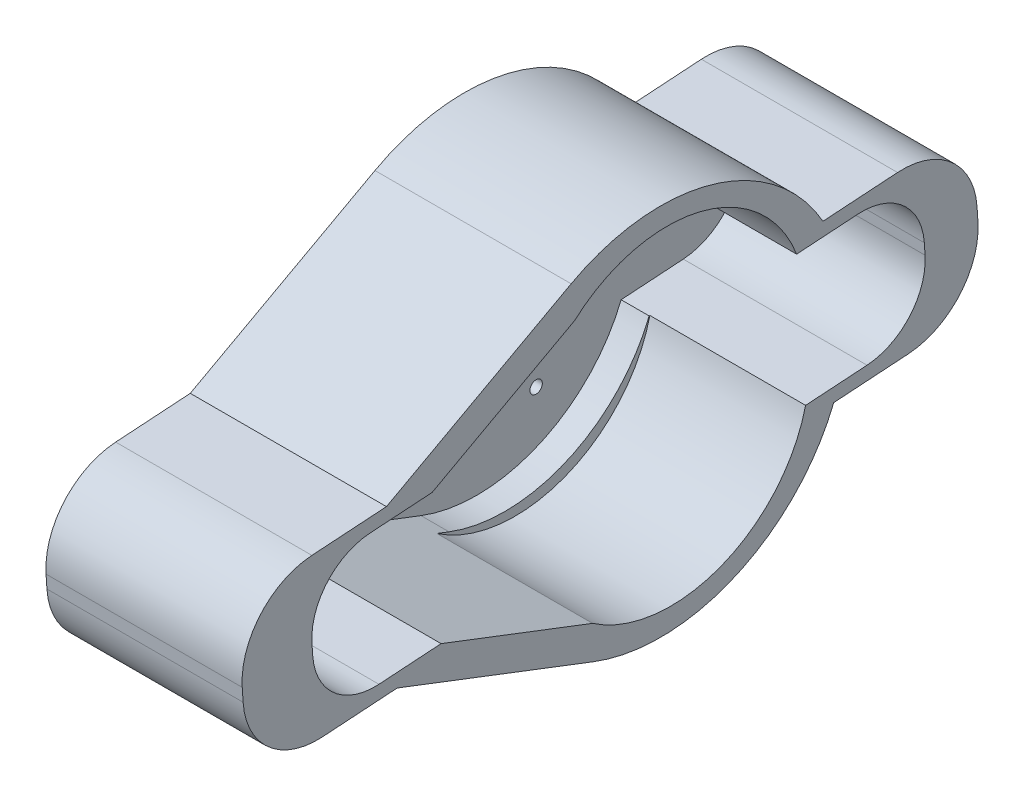
SolidWorks part; units mm, degrees
ref_plane "Front Plane" through (0, 0, 0) normal (0, 0, 1) x (1, 0, 0)
ref_plane "Top Plane" through (0, 0, 0) normal (0, 1, 0) x (1, 0, 0)
ref_plane "Right Plane" through (0, 0, 0) normal (1, 0, 0) x (0, 0, -1)
sketch "Sketch1" plane through (15, 0, 0) normal (1, 0, 0) x (0, 0, -1)
  line L0 (3.2178, 50.6772) -> (3.0998, 52.461) construction
  line L1 (-95.2193, 45.9576) -> (-95.1013, 44.1738) construction
  line L2 (-84.4631, 34.8556) -> (-74.4849, 35.5156) construction
  line L3 (-74.4849, 35.5156) -> (-48.2133, 25.4259) construction
  line L4 (-16.0786, 39.379) -> (-6.1004, 40.039) construction
  line L5 (-7.5384, 61.7792) -> (-17.5166, 61.1192) construction
  line L6 (-75.9229, 57.2559) -> (-85.9011, 56.5958) construction
  line L7 (-51.2092, 70.7181) -> (-75.9229, 57.2559) construction
  line L8 (3.2178, 50.6772) -> (3.0998, 52.461)
  line L9 (-95.2193, 45.9576) -> (-95.1013, 44.1738)
  line L10 (-84.4631, 34.8556) -> (-74.4849, 35.5156)
  line L11 (-74.4849, 35.5156) -> (-48.2133, 25.4259)
  line L12 (-16.0786, 39.379) -> (-6.1004, 40.039)
  line L13 (-7.5384, 61.7792) -> (-17.5166, 61.1192)
  line L14 (-75.9229, 57.2559) -> (-85.9011, 56.5958)
  line L15 (-51.2092, 70.7181) -> (-75.9229, 57.2559)
  line L24 (11.7114, 51.0599) -> (11.5698, 53.2005)
  line L25 (-106.4131, 45.3964) -> (-106.2715, 43.2558)
  line L26 (-93.5056, 32.0739) -> (-81.5318, 32.866)
  line L27 (-81.5318, 32.866) -> (-50.0059, 20.7583)
  line L28 (-11.4443, 37.502) -> (0.5295, 38.294)
  line L29 (-1.1961, 64.3823) -> (-13.1699, 63.5903)
  line L30 (-83.2574, 58.9542) -> (-95.2313, 58.1622)
  line L31 (-53.6009, 75.1089) -> (-83.2574, 58.9542)
  arc A0 (-85.9011, 56.5958) -> (-95.2193, 45.9576) centre (-85.2411, 46.6176) ccw construction
  arc A1 (-95.1013, 44.1738) -> (-84.4631, 34.8556) centre (-85.1231, 44.8338) ccw construction
  arc A2 (-48.2133, 25.4259) -> (-16.0786, 39.379) centre (-39.2502, 48.7639) ccw construction
  arc A3 (-6.1004, 40.039) -> (3.2178, 50.6772) centre (-6.7604, 50.0172) ccw construction
  arc A4 (3.0998, 52.461) -> (-7.5384, 61.7792) centre (-6.8784, 51.801) ccw construction
  arc A5 (-17.5166, 61.1192) -> (-51.2092, 70.7181) centre (-39.2502, 48.7639) ccw construction
  arc A6 (-85.9011, 56.5958) -> (-95.2193, 45.9576) centre (-85.2411, 46.6176) ccw
  arc A7 (-95.1013, 44.1738) -> (-84.4631, 34.8556) centre (-85.1231, 44.8338) ccw
  arc A8 (-48.2133, 25.4259) -> (-16.0786, 39.379) centre (-39.2502, 48.7639) ccw
  arc A9 (-6.1004, 40.039) -> (3.2178, 50.6772) centre (-6.7604, 50.0172) ccw
  arc A10 (3.0998, 52.461) -> (-7.5384, 61.7792) centre (-6.8784, 51.801) ccw
  arc A11 (-17.5166, 61.1192) -> (-51.2092, 70.7181) centre (-39.2502, 48.7639) ccw
  arc A18 (-95.2313, 58.1622) -> (-106.4131, 45.3964) centre (-94.4393, 46.1884) ccw
  arc A19 (-106.2715, 43.2558) -> (-93.5056, 32.0739) centre (-94.2977, 44.0478) ccw
  arc A20 (-50.0059, 20.7583) -> (-11.4443, 37.502) centre (-39.2502, 48.7639) ccw
  arc A21 (0.5295, 38.294) -> (11.7114, 51.0599) centre (-0.2625, 50.2678) ccw
  arc A22 (11.5698, 53.2005) -> (-1.1961, 64.3823) centre (-0.4041, 52.4084) ccw
  arc A23 (-13.1699, 63.5903) -> (-53.6009, 75.1089) centre (-39.2502, 48.7639) ccw
extrude "Boss-Extrude1" add sketch "Sketch1" against normal up to surface (29.5 mm away)
sketch "Sketch2" plane through (15, 0, 0) normal (1, 0, 0) x (0, 0, -1)
  line L0 (-114.8887, 43.7608) -> (21.8126, 52.803) construction
  line L1 (-115.1857, 48.2509) -> (-114.5917, 39.2706) construction
  line L2 (22.1096, 48.3128) -> (21.5156, 57.2932) construction
  line L3 (-46.5381, 48.2819) -> (-49.4407, 92.1637) construction
  line L4 (-87.8309, 69.1019) -> (-6.7916, 74.4623) construction
  line L5 (-29.272, 49.424) -> (-32.265, 94.6726) construction
  line L6 (-30.7942, 72.8746) -> (-46.5381, 48.2819) construction
  line L7 (-50.8646, 71.547) -> (-29.272, 49.424) construction
  line L8 (-40.1348, 82.781) -> (-37.3716, 41.0075) construction
  arc A0 (-39.0466, 63.8102) -> (-56.0096, 62.6882) centre (-47.5281, 63.2492) ccw construction
  circle A1 centre (-38.1763, 53.1732) radius 22.247
  circle A2 centre (-37.6049, 44.5345) radius 22.247
  point P21 (-38.6661, 60.5782)
  arc M9 (-16.0786, 39.379) -> (-48.2133, 25.4259) centre (-39.2502, 48.7639) cw
  line M10 (-48.2133, 25.4259) -> (-74.4849, 35.5156)
  line M16 (-75.9229, 57.2559) -> (-51.2092, 70.7181)
  arc M17 (-51.2092, 70.7181) -> (-17.5166, 61.1192) centre (-39.2502, 48.7639) cw
  dimension "D2" = 44.494
  dimension "D1" = 10
extrude "Cut-Extrude1" cut sketch "Sketch2" against normal up to surface (25 mm away) contours A1 M17 M16 | A1 A2 M17 M16 | A2 A1 | A2 A1 M10 M9 | A2 M9 M10
sketch "Sketch3" plane through (-14.5, 0, 0) normal (-1, 0, 0) x (0, 0, 1)
  line L0 (83.2574, 58.9542) -> (53.6009, 75.1089) construction
  line L1 (95.2313, 58.1622) -> (83.2574, 58.9542) construction
  line L2 (106.2715, 43.2558) -> (106.4131, 45.3964) construction
  line L3 (81.5318, 32.866) -> (93.5056, 32.0739) construction
  line L4 (50.0059, 20.7583) -> (81.5318, 32.866) construction
  line L5 (-0.5295, 38.294) -> (11.4443, 37.502) construction
  line L6 (-11.5698, 53.2005) -> (-11.7114, 51.0599) construction
  line L7 (13.1699, 63.5903) -> (1.1961, 64.3823) construction
  line L8 (83.2574, 58.9542) -> (53.6009, 75.1089)
  line L9 (95.2313, 58.1622) -> (83.2574, 58.9542)
  line L10 (106.2715, 43.2558) -> (106.4131, 45.3964)
  line L11 (81.5318, 32.866) -> (93.5056, 32.0739)
  line L12 (50.0059, 20.7583) -> (81.5318, 32.866)
  line L13 (-0.5295, 38.294) -> (11.4443, 37.502)
  line L14 (-11.5698, 53.2005) -> (-11.7114, 51.0599)
  line L15 (13.1699, 63.5903) -> (1.1961, 64.3823)
  arc A0 (53.6009, 75.1089) -> (13.1699, 63.5903) centre (39.2502, 48.7639) ccw construction
  arc A1 (106.4131, 45.3964) -> (95.2313, 58.1622) centre (94.4393, 46.1884) ccw construction
  arc A2 (93.5056, 32.0739) -> (106.2715, 43.2558) centre (94.2977, 44.0478) ccw construction
  arc A3 (11.4443, 37.502) -> (50.0059, 20.7583) centre (39.2502, 48.7639) ccw construction
  arc A4 (-11.7114, 51.0599) -> (-0.5295, 38.294) centre (0.2625, 50.2678) ccw construction
  arc A5 (1.1961, 64.3823) -> (-11.5698, 53.2005) centre (0.4041, 52.4084) ccw construction
  arc A6 (53.6009, 75.1089) -> (13.1699, 63.5903) centre (39.2502, 48.7639) ccw
  arc A7 (106.4131, 45.3964) -> (95.2313, 58.1622) centre (94.4393, 46.1884) ccw
  arc A8 (93.5056, 32.0739) -> (106.2715, 43.2558) centre (94.2977, 44.0478) ccw
  arc A9 (11.4443, 37.502) -> (50.0059, 20.7583) centre (39.2502, 48.7639) ccw
  arc A10 (-11.7114, 51.0599) -> (-0.5295, 38.294) centre (0.2625, 50.2678) ccw
  arc A11 (1.1961, 64.3823) -> (-11.5698, 53.2005) centre (0.4041, 52.4084) ccw
  arc A12 (74.2645, 44.8237) -> (66.1007, 48.612) centre (70.1826, 46.7179) ccw construction
  arc A13 (74.2645, 44.8237) -> (66.1007, 48.612) centre (70.1826, 46.7179) ccw
  arc A14 (66.1007, 48.612) -> (74.2645, 44.8237) centre (70.1826, 46.7179) ccw
extrude "Boss-Extrude2" add sketch "Sketch3" along normal up to surface (2 mm away)
sketch "Sketch4" plane through (-10, 0, 0) normal (1, 0, 0) x (0, 0, -1)
  arc A0 (-73.4188, 51.8307) -> (-71.9974, 52.4903) centre (-72.7081, 52.1605) ccw construction
  arc A1 (-73.4188, 51.8307) -> (-71.9974, 52.4903) centre (-72.7081, 52.1605) ccw
  arc A2 (-64.0293, 49.5732) -> (-65.4507, 48.9136) centre (-64.74, 49.2434) ccw construction
  arc A3 (-64.0293, 49.5732) -> (-65.4507, 48.9136) centre (-64.74, 49.2434) ccw
  arc A4 (-74.9145, 44.5221) -> (-76.3359, 43.8626) centre (-75.6252, 44.1923) ccw construction
  arc A5 (-74.9145, 44.5221) -> (-76.3359, 43.8626) centre (-75.6252, 44.1923) ccw
  arc A6 (-66.9464, 41.6051) -> (-68.3678, 40.9455) centre (-67.6571, 41.2753) ccw construction
  arc A7 (-66.9464, 41.6051) -> (-68.3678, 40.9455) centre (-67.6571, 41.2753) ccw
  arc A8 (-73.4188, 51.8307) -> (-71.9974, 52.4903) centre (-72.7081, 52.1605) cw
  arc A9 (-65.4507, 48.9136) -> (-64.0293, 49.5732) centre (-64.74, 49.2434) ccw
  arc A10 (-68.3678, 40.9455) -> (-66.9464, 41.6051) centre (-67.6571, 41.2753) ccw
  arc A11 (-76.3359, 43.8626) -> (-74.9145, 44.5221) centre (-75.6252, 44.1923) ccw
extrude "Cut-Extrude2" cut sketch "Sketch4" against normal through all
sketch "Sketch5" plane through (-10, 0, 0) normal (1, 0, 0) x (0, 0, -1)
  circle A0 centre (-72.7081, 52.1605) radius 1.775
  circle A1 centre (-64.74, 49.2434) radius 1.775
  circle A2 centre (-67.6571, 41.2753) radius 1.775
  circle A3 centre (-75.6252, 44.1923) radius 1.775
  circle A4 centre (-75.6252, 44.1923) radius 0.7835 construction
  circle A5 centre (-67.6571, 41.2753) radius 0.7835 construction
  circle A7 centre (-64.74, 49.2434) radius 0.7835 construction
  circle A8 centre (-72.7081, 52.1605) radius 0.7835 construction
  point P15 (0, 0)
  point P16 (0, 0)
  dimension "D1" = 3.55
extrude "Cut-Extrude4" cut sketch "Sketch5" against normal blind 5.5
sketch "Sketch6" plane through (-14.5, 0, 0) normal (1, 0, 0) x (0, 0, -1)
  circle A0 centre (-29.7297, 34.0803) radius 1
  circle A1 centre (-53.9338, 39.2434) radius 1
  circle A2 centre (-24.5666, 58.2845) radius 1
  circle A3 centre (-48.7707, 63.4476) radius 1
extrude "Cut-Extrude5" cut sketch "Sketch6" against normal through all
